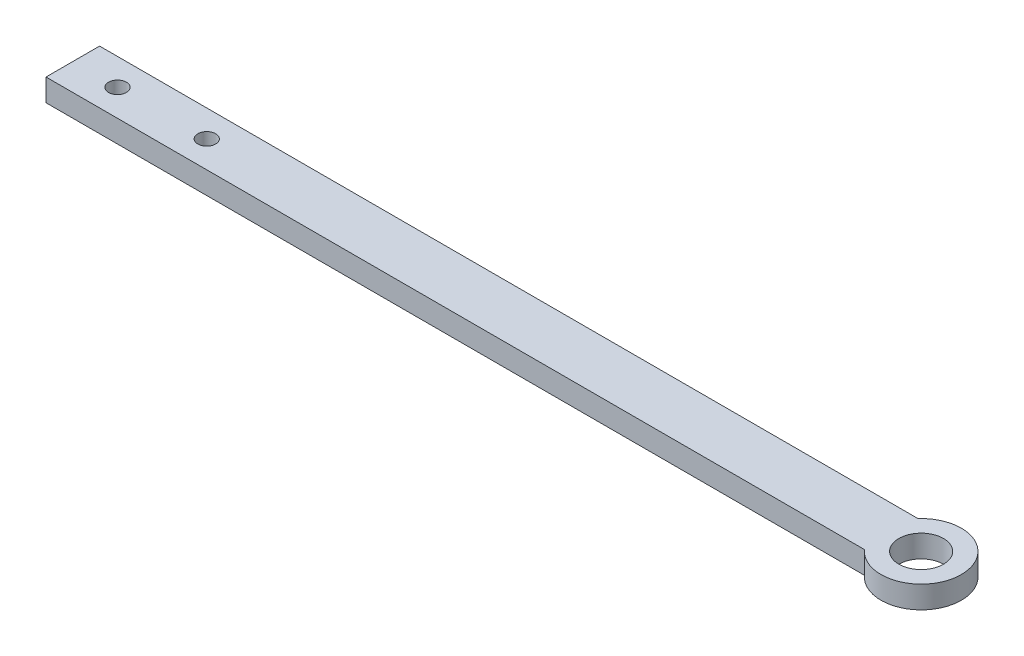
SolidWorks part; units mm, degrees
ref_plane "Front Plane" through (0, 0, 0) normal (0, 0, 1) x (1, 0, 0)
ref_plane "Top Plane" through (0, 0, 0) normal (0, 1, 0) x (1, 0, 0)
ref_plane "Right Plane" through (0, 0, 0) normal (1, 0, 0) x (0, 0, -1)
sketch "Sketch1" plane through (0, 0, 0) normal (0, 1, 0) x (1, 0, 0)
  line L0 (-6.7082, 6) -> (-190, 6)
  line L1 (-190, 6) -> (-190, -6)
  line L2 (-190, -6) -> (-6.7082, -6)
  arc A0 (-6.7082, -6) -> (-6.7082, 6) centre (0, 0) ccw
  dimension "D1" = 18
  dimension "D2" = 6
  dimension "D3" = 190
extrude "Boss-Extrude1" add sketch "Sketch1" along normal blind 5
sketch "Sketch2" plane through (0, 5, 0) normal (0, 1, 0) x (1, 0, 0)
  line L0 (-190, 6) -> (-190, -6) construction
  circle A0 centre (0, 0) radius 5
  circle A1 centre (-180, 0) radius 2
  circle A2 centre (-160, 0) radius 2
  dimension "D1" = 10
  dimension "D2" = 4
  dimension "D3" = 10
  dimension "D4" = 20
extrude "Cut-Extrude1" cut sketch "Sketch2" against normal through all
